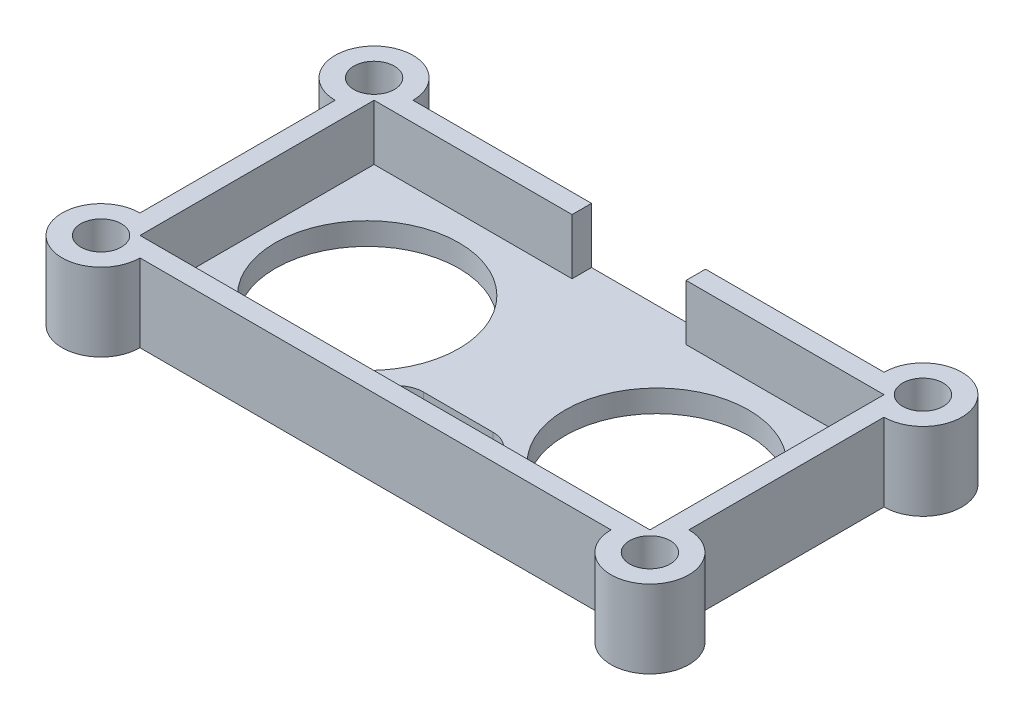
SolidWorks part; units mm, degrees
ref_plane "Front Plane" through (0, 0, 0) normal (0, 0, 1) x (1, 0, 0)
ref_plane "Top Plane" through (0, 0, 0) normal (0, 1, 0) x (1, 0, 0)
ref_plane "Right Plane" through (0, 0, 0) normal (1, 0, 0) x (0, 0, -1)
sketch "Sketch1" plane through (0, 0, 0) normal (0, 1, 0) x (1, 0, 0)
  line L1 (-24.675, 12.275) -> (24.675, 12.275)
  line L2 (-24.675, 12.275) -> (-24.675, -12.275)
  line L3 (-24.675, -12.275) -> (24.675, -12.275)
  line L4 (24.675, 12.275) -> (24.675, -12.275)
  dimension "D1" = 49.35
  dimension "D2" = 24.675
  dimension "D3" = 24.55
  dimension "D4" = 12.275
extrude "Boss-Extrude1" add sketch "Sketch1" along normal blind 2
sketch "Sketch2" plane through (0, 2, 0) normal (0, 1, 0) x (1, 0, 0)
  line L0 (-24.675, 12.275) -> (-24.675, -12.275)
  line L1 (-24.675, -12.275) -> (24.675, -12.275)
  line L2 (24.675, -12.275) -> (24.675, 12.275)
  line L3 (24.675, 12.275) -> (5.125, 12.275)
  line L4 (24.675, 12.275) -> (-24.675, 12.275) construction
  line L5 (5.125, 12.275) -> (5.125, 10.525)
  line L6 (5.125, 10.525) -> (22.925, 10.525)
  line L7 (22.925, 10.525) -> (22.925, -10.525)
  line L8 (22.925, -10.525) -> (-22.925, -10.525)
  line L9 (-22.925, -10.525) -> (-22.925, 10.525)
  line L10 (-22.925, 10.525) -> (-5.125, 10.525)
  line L11 (-5.125, 10.525) -> (-5.125, 12.275)
  line L12 (-5.125, 12.275) -> (-24.675, 12.275)
  dimension "D1" = 19.55
  dimension "D2" = 1.75
  dimension "D3" = 1.75
  dimension "D4" = 1.75
  dimension "D5" = 1.75
  dimension "D6" = 1.75
  dimension "D7" = 19.55
extrude "Boss-Extrude2" add sketch "Sketch2" along normal blind 5
sketch "Sketch4" plane through (0, 2, 0) normal (0, 1, 0) x (1, 0, 0)
  line L0 (-24.675, 12.275) -> (-24.675, 8.775)
  line L1 (-24.675, 12.275) -> (-21.175, 12.275)
  line L2 (-24.675, -12.275) -> (-24.675, -8.775)
  line L3 (-24.675, -12.275) -> (-21.175, -12.275)
  line L4 (24.675, -12.275) -> (21.175, -12.275)
  line L5 (24.675, -12.275) -> (24.675, -8.775)
  line L6 (24.675, 8.775) -> (24.675, 12.275)
  line L7 (24.675, 12.275) -> (21.175, 12.275)
  arc A0 (-21.175, 12.275) -> (-24.675, 8.775) centre (-24.675, 12.275) ccw
  arc A1 (-24.675, -8.775) -> (-21.175, -12.275) centre (-24.675, -12.275) ccw
  arc A2 (21.175, -12.275) -> (24.675, -8.775) centre (24.675, -12.275) ccw
  arc A3 (24.675, 8.775) -> (21.175, 12.275) centre (24.675, 12.275) ccw
  dimension "D1" = 7
  dimension "D2" = 7
  dimension "D3" = 7
  dimension "D4" = 7
extrude "Boss-Extrude3" add sketch "Sketch4" along normal up to surface and the other way up to surface
sketch "Sketch3" plane through (0, 2, 0) normal (0, 1, 0) x (1, 0, 0)
  line L0 (-3, -7.35) -> (3.25, -7.35) construction
  line L1 (-3, -4.975) -> (3.25, -4.975)
  line L2 (-3, -9.725) -> (3.25, -9.725)
  line L5 (-22.925, -10.525) -> (-22.925, 10.525) construction
  line L7 (22.925, 10.525) -> (22.925, -10.525) construction
  line L9 (22.925, -10.525) -> (-22.925, -10.525) construction
  line L11 (22.925, -10.525) -> (-22.925, -10.525) construction
  line L12 (-22.925, -10.525) -> (-22.925, 10.525) construction
  circle A0 centre (-13.025, 0) radius 8.25
  circle A1 centre (13.025, 0) radius 8.25
  arc A2 (-3, -4.975) -> (-3, -9.725) centre (-3, -7.35) ccw
  arc A3 (3.25, -9.725) -> (3.25, -4.975) centre (3.25, -7.35) ccw
  circle A4 centre (-24.675, 12.275) radius 1.825
  circle A5 centre (-24.675, -12.275) radius 1.825
  circle A6 centre (24.675, 12.275) radius 1.825
  circle A7 centre (24.675, -12.275) radius 1.825
  point P6 (0.125, -7.35)
  point P16 (-22.925, 0)
  point P18 (22.925, 0)
  point P23 (-5.375, -7.35)
  point P24 (5.625, -7.35)
  dimension "D1" = 16.5
  dimension "D2" = 16.5
  dimension "D11" = 3.65
  dimension "D12" = 3.65
  dimension "D13" = 3.65
  dimension "D14" = 3.65
  dimension "D3" = 9.9
  dimension "D4" = 9.9
  dimension "D5" = 10.525
  dimension "D6" = 10.525
  dimension "D7" = 4.75
  dimension "D8" = 0.8
  dimension "D9" = 11
  dimension "D10" = 17.55
extrude "Cut-Extrude1" cut sketch "Sketch3" against normal through all and the other way through all
